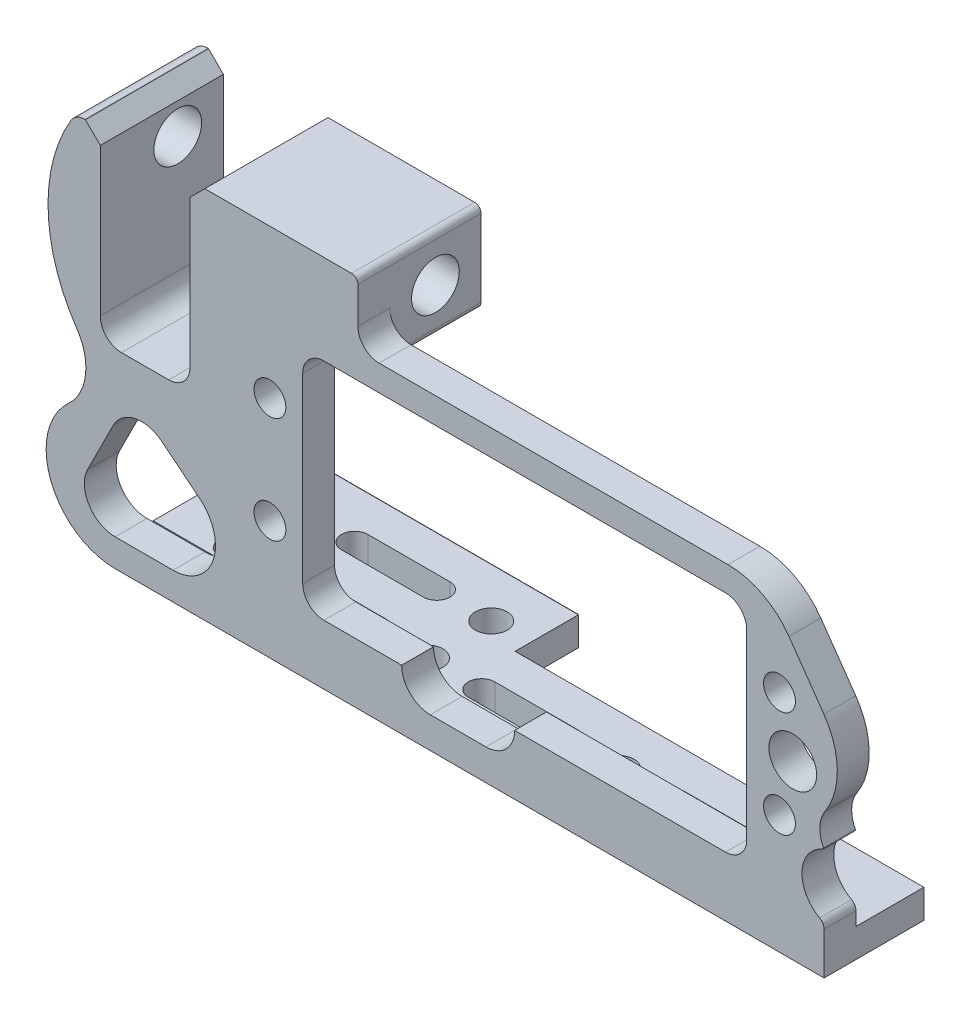
SolidWorks part; units mm, degrees
ref_plane "前视基准面" through (0, 0, 0) normal (0, 0, 1) x (1, 0, 0)
ref_plane "上视基准面" through (0, 0, 0) normal (0, 1, 0) x (1, 0, 0)
ref_plane "右视基准面" through (0, 0, 0) normal (1, 0, 0) x (0, 0, -1)
other "Configuration Table"
ref_plane "基准面1" through (0, 0, -7.725) normal (0, 0, -1) x (-1, 0, 0)
sketch "草图1" plane through (0, 0, -7.725) normal (0, 0, -1) x (-1, 0, 0)
  line L0 (33.1, 4.5) -> (24.8243, 4.5)
  line L1 (25.7249, 9.7195) -> (29.3009, 12.5896)
  line L2 (33.859, 11.5975) -> (36.2697, 6.8026)
  line L3 (33.6787, 2.6) -> (33.1, 2.6)
  line L4 (33.1, 2.6) -> (33.1, 4.5)
  line L5 (-33.1, 4.5) -> (-33.1, 0)
  line L6 (-33.1, 0) -> (33.6787, 0)
  line L7 (37.38, 35.225) -> (10.81, 35.225)
  line L8 (10.81, 35.225) -> (10.81, 29.2)
  line L9 (10.81, 29.2) -> (-27.6994, 29.2)
  line L10 (-27.6994, 29.2) -> (-33.0805, 21.515)
  arc A0 (24.8243, 4.5) -> (25.7249, 9.7195) centre (28.2287, 6.6) cw
  arc A1 (29.3009, 12.5896) -> (33.859, 11.5975) centre (31.1787, 10.25) cw
  arc A2 (36.2697, 6.8026) -> (33.6787, 2.6) centre (33.6787, 5.5) cw
  arc A3 (-33.1, 10.5) -> (-33.1, 4.5) centre (-34.2136, 7.5) cw
  arc A4 (33.6787, 0) -> (38.0616, 11.3) centre (33.6787, 6.5) ccw
  arc A5 (38.0616, 11.3) -> (37.2993, 17.8052) centre (41.433, 14.9924) cw
  arc A6 (37.2993, 17.8052) -> (37.38, 35.225) centre (24.4109, 26.575) ccw
  arc A7 (-33.0805, 21.515) -> (-33.1926, 13.65) centre (-27.3464, 17.5) ccw
  arc A8 (-33.1926, 13.65) -> (-33.1, 10.5) centre (-35.6981, 12) cw
extrude "凸台-拉伸1" add sketch "草图1" against normal blind 15.45
sketch "草图2" plane through (0, 0, 7.725) normal (0, 0, 1) x (1, 0, 0)
  line L0 (-33.1, 2.7) -> (-33.1, 2.6)
  line L1 (-33.1, 2.6) -> (-28.2287, 2.6)
  line L2 (-24.8243, 4.5) -> (-33.1, 4.5)
  line L3 (-33.1, 4.5) -> (-33.1, 2.7)
  arc A0 (-28.2287, 2.6) -> (-24.8243, 4.5) centre (-28.2287, 6.6) ccw
extrude "切除-拉伸1" cut sketch "草图2" against normal blind 3
sketch "草图3" plane through (0, 0, -7.725) normal (0, 0, -1) x (-1, 0, 0)
  line L0 (37.38, 35.225) -> (10.81, 35.225)
  line L1 (10.81, 35.225) -> (10.81, 29.2)
  line L2 (10.81, 29.2) -> (-27.6994, 29.2)
  line L3 (-27.6994, 29.2) -> (-33.0805, 21.515)
  line L4 (-33.1, 4.5) -> (24.8243, 4.5)
  line L5 (25.7249, 9.7195) -> (29.3009, 12.5896)
  line L6 (33.859, 11.5975) -> (36.2697, 6.8026)
  line L7 (33.6787, 2.6) -> (33.1, 2.6)
  line L8 (33.1, 2.6) -> (33.1, 0)
  line L9 (33.1, 0) -> (33.6787, 0)
  arc A0 (33.6787, 0) -> (38.0616, 11.3) centre (33.6787, 6.5) ccw
  arc A1 (38.0616, 11.3) -> (37.2993, 17.8052) centre (41.433, 14.9924) cw
  arc A2 (37.2993, 17.8052) -> (37.38, 35.225) centre (24.4109, 26.575) ccw
  arc A3 (-33.0805, 21.515) -> (-33.1926, 13.65) centre (-27.3464, 17.5) ccw
  arc A4 (-33.1926, 13.65) -> (-33.1, 10.5) centre (-35.6981, 12) cw
  arc A5 (-33.1, 10.5) -> (-33.1, 4.5) centre (-34.2136, 7.5) cw
  arc A6 (24.8243, 4.5) -> (25.7249, 9.7195) centre (28.2287, 6.6) cw
  arc A7 (29.3009, 12.5896) -> (33.859, 11.5975) centre (31.1787, 10.25) cw
  arc A8 (36.2697, 6.8026) -> (33.6787, 2.6) centre (33.6787, 5.5) cw
extrude "切除-拉伸2" cut sketch "草图3" against normal blind 3.85
ref_plane "基准面2" through (0, 5.625, 0) normal (0, -1, 0) x (1, 0, 0)
sketch "草图4" plane through (0, 5.625, 0) normal (0, -1, 0) x (1, 0, 0)
  line L0 (-16.01, -3.875) -> (25.81, -3.875)
  line L1 (25.81, -3.875) -> (25.81, 7.725)
  line L2 (25.81, 7.725) -> (-16.01, 7.725)
  line L3 (-16.01, 7.725) -> (-16.01, -3.875)
extrude "切除-拉伸3" cut sketch "草图4" against normal blind 21.15
sketch "草图5" plane through (0, 0, -3.875) normal (0, 0, -1) x (-1, 0, 0)
  line L0 (-33.1, 4.5) -> (24.8243, 4.5)
  line L1 (25.7249, 9.7195) -> (29.3009, 12.5896)
  line L2 (33.859, 11.5975) -> (36.2697, 6.8026)
  line L3 (33.6787, 2.6) -> (33.1, 2.6)
  line L4 (33.1, 2.6) -> (33.1, 0)
  line L5 (33.1, 0) -> (33.6787, 0)
  line L6 (36.4923, 14.225) -> (31.8022, 14.225)
  line L7 (25.2221, 26.775) -> (16.01, 26.775)
  line L8 (16.01, 26.775) -> (16.01, 5.625)
  line L9 (16.01, 5.625) -> (-25.81, 5.625)
  line L10 (-25.81, 5.625) -> (-25.81, 26.775)
  line L11 (-25.81, 26.775) -> (10.81, 26.775)
  line L12 (10.81, 26.775) -> (10.81, 29.2)
  line L13 (10.81, 29.2) -> (-27.6994, 29.2)
  line L14 (-27.6994, 29.2) -> (-33.0805, 21.515)
  arc A0 (24.8243, 4.5) -> (25.7249, 9.7195) centre (28.2287, 6.6) cw
  arc A1 (29.3009, 12.5896) -> (33.859, 11.5975) centre (31.1787, 10.25) cw
  arc A2 (36.2697, 6.8026) -> (33.6787, 2.6) centre (33.6787, 5.5) cw
  arc A3 (33.6787, 0) -> (38.0616, 11.3) centre (33.6787, 6.5) ccw
  arc A4 (38.0616, 11.3) -> (36.4923, 14.225) centre (41.433, 14.9924) cw
  arc A5 (31.8022, 14.225) -> (25.2221, 26.775) centre (31.8022, 22.225) cw
  arc A6 (-33.0805, 21.515) -> (-33.1926, 13.65) centre (-27.3464, 17.5) ccw
  arc A7 (-33.1926, 13.65) -> (-33.1, 10.5) centre (-35.6981, 12) cw
  arc A8 (-33.1, 10.5) -> (-33.1, 4.5) centre (-34.2136, 7.5) cw
extrude "切除-拉伸4" cut sketch "草图5" against normal blind 8.6
sketch "草图6" plane through (0, 4.5, 0) normal (0, 1, 0) x (-1, 0, 0)
  line L0 (-33.1, 4.725) -> (-33.1, -7.725)
  line L1 (-33.1, -7.725) -> (33.1, -7.725)
  line L2 (33.1, -7.725) -> (33.1, 4.725)
  line L3 (33.1, 4.725) -> (27.3399, 4.725)
  line L4 (27.3399, 4.725) -> (-33.1, 4.725)
extrude "切除-拉伸5" cut sketch "草图6" against normal blind 1.8
sketch "草图7" plane through (0, 0, 4.725) normal (0, 0, -1) x (-1, 0, 0)
  line L0 (6.69, 5.625) -> (-3.95, 5.625)
  line L1 (-1.25, 2.925) -> (3.99, 2.925)
  arc A0 (-3.95, 5.625) -> (-1.25, 2.925) centre (-1.25, 5.625) ccw
  arc A1 (3.99, 2.925) -> (6.69, 5.625) centre (3.99, 5.625) ccw
extrude "切除-拉伸6" cut sketch "草图7" against normal through all
sketch "草图8" plane through (0, 0, 0) normal (0, -1, 0) x (1, 0, 0)
  line L0 (33.1, -1.675) -> (-5.4, -1.675)
  line L1 (-5.4, -1.675) -> (-5.4, -7.725)
  line L2 (-5.4, -7.725) -> (33.1, -7.725)
  line L3 (33.1, -7.725) -> (33.1, -1.675)
extrude "切除-拉伸7" cut sketch "草图8" against normal through all
sketch "草图9" plane through (0, 0, 7.725) normal (0, 0, 1) x (1, 0, 0)
  line L0 (-26.63, 35.225) -> (-36.48, 35.225)
  line L1 (-36.48, 35.225) -> (-35.08, 33.825)
  line L2 (-35.08, 33.825) -> (-35.08, 17.925)
  line L3 (-35.08, 17.925) -> (-26.63, 17.925)
  line L4 (-26.63, 17.925) -> (-26.63, 35.225)
extrude "切除-拉伸8" cut sketch "草图9" against normal through all
sketch "草图10" plane through (0, 2.7, 0) normal (0, 1, 0) x (-1, 0, 0)
  line L0 (3.865, 4.275) -> (-3.865, 4.275)
  line L1 (-3.865, 1.775) -> (3.865, 1.775)
  arc A0 (-3.865, 4.275) -> (-3.865, 1.775) centre (-3.865, 3.025) ccw
  arc A1 (3.865, 1.775) -> (3.865, 4.275) centre (3.865, 3.025) ccw
extrude "切除-拉伸9" cut sketch "草图10" against normal through all
sketch "草图11" plane through (0, 2.7, 0) normal (0, 1, 0) x (-1, 0, 0)
  line L0 (-14.135, 4.275) -> (-21.865, 4.275)
  line L1 (-21.865, 1.775) -> (-14.135, 1.775)
  arc A0 (-21.865, 4.275) -> (-21.865, 1.775) centre (-21.865, 3.025) ccw
  arc A1 (-14.135, 1.775) -> (-14.135, 4.275) centre (-14.135, 3.025) ccw
extrude "切除-拉伸10" cut sketch "草图11" against normal through all
sketch "草图12" plane through (0, 2.7, 0) normal (0, 1, 0) x (-1, 0, 0)
  line L0 (14.135, -4.275) -> (21.865, -4.275)
  line L1 (21.865, -1.775) -> (14.135, -1.775)
  arc A0 (14.135, -1.775) -> (14.135, -4.275) centre (14.135, -3.025) ccw
  arc A1 (21.865, -4.275) -> (21.865, -1.775) centre (21.865, -3.025) ccw
extrude "切除-拉伸11" cut sketch "草图12" against normal through all
sketch "草图13" plane through (0, 0, 0) normal (0, -1, 0) x (1, 0, 0)
  line L0 (-14.135, 4.275) -> (-21.865, 4.275)
  line L1 (-21.865, 1.775) -> (-14.135, 1.775)
  arc A0 (-21.865, 4.275) -> (-21.865, 1.775) centre (-21.865, 3.025) ccw
  arc A1 (-14.135, 1.775) -> (-14.135, 4.275) centre (-14.135, 3.025) ccw
extrude "切除-拉伸12" cut sketch "草图13" against normal up to next
hole_wizard "Ø4.5 (4.5) 直径孔1" positions "草图15" profile "草图14" hole size "Ø4.5" standard "ANSI Metric"
sketch "草图15" plane through (0, 0, 7.725) normal (0, 0, 1) x (1, 0, 0)
  point P0 (30.15, 16.2)
sketch "草图14" plane through (30.15, 16.2, 7.725) normal (1, 0, 0) x (0, -1, 0)
  line L0 (0, 0) -> (0, 15.45)
  line L1 (0, 15.45) -> (2.25, 15.45)
  line L2 (2.25, 15.45) -> (2.25, 0)
  line L5 (2.25, 0) -> (0, 0)
  line L11 (0, -6.35) -> (0, 107.95) construction
  dimension "通孔孔直径" = 4.5
  dimension "通孔孔深度" = 15.45
hole_wizard "Ø3.0 (3) 直径孔1" positions "草图17" profile "草图16" hole size "Ø3.0" standard "ANSI Metric"
sketch "草图17" plane through (0, 0, 7.725) normal (0, 0, 1) x (1, 0, 0)
  point P0 (-19.1, 11.2)
  point P1 (28.9, 11.2)
  point P2 (-19.1, 21.2)
  point P3 (28.9, 21.2)
sketch "草图16" plane through (-19.1, 11.2, 7.725) normal (1, 0, 0) x (0, -1, 0)
  line L0 (0, 0) -> (0, 15.45)
  line L1 (0, 15.45) -> (1.5, 15.45)
  line L2 (1.5, 15.45) -> (1.5, 0)
  line L5 (1.5, 0) -> (0, 0)
  line L11 (0, -6.35) -> (0, 107.95) construction
  dimension "通孔孔直径" = 3
  dimension "通孔孔深度" = 15.45
hole_wizard "Ø4.5 (4.5) 直径孔2" positions "草图19" profile "草图18" hole size "Ø4.5" standard "ANSI Metric"
sketch "草图19" plane through (-10.81, 0, 0) normal (1, 0, 0) x (0, 0, -1)
  point P0 (-0.425, 30.925)
sketch "草图18" plane through (-10.81, 30.925, 0.425) normal (0, 1, 0) x (0, 0, -1)
  line L0 (0, 0) -> (0, 15.82)
  line L1 (0, 15.82) -> (2.25, 15.82)
  line L2 (2.25, 15.82) -> (2.25, 0)
  line L5 (2.25, 0) -> (0, 0)
  line L11 (0, -6.35) -> (0, 107.95) construction
  dimension "通孔孔直径" = 4.5
  dimension "通孔孔深度" = 15.82
hole_wizard "Ø3.0 (3) 直径孔2" positions "草图21" profile "草图20" hole size "Ø3.0" standard "ANSI Metric"
sketch "草图21" plane through (0, 0, 0) normal (0, -1, 0) x (-1, 0, 0)
  point P0 (-9, -3.025)
  point P1 (9, -3.025)
  point P2 (9, 3.025)
  point P3 (-27, -3.025)
sketch "草图20" plane through (9, 0, 3.025) normal (1, 0, 0) x (0, 0, -1)
  line L0 (0, 0) -> (0, 35.225)
  line L1 (0, 35.225) -> (1.5, 35.225)
  line L2 (1.5, 35.225) -> (1.5, 0)
  line L5 (1.5, 0) -> (0, 0)
  line L11 (0, -6.35) -> (0, 107.95) construction
  dimension "通孔孔直径" = 3
  dimension "通孔孔深度" = 35.225
hole_wizard "Ø3.0 (3) 直径孔3" positions "草图23" profile "草图22" hole size "Ø3.0" standard "ANSI Metric"
sketch "草图23" plane through (0, 0, 0) normal (0, -1, 0) x (-1, 0, 0)
  point P0 (27, -3.025)
  point P1 (27, 3.025)
sketch "草图22" plane through (-27, 0, 3.025) normal (1, 0, 0) x (0, 0, -1)
  line L0 (0, 0) -> (0, 2.7)
  line L1 (0, 2.7) -> (1.5, 2.7)
  line L2 (1.5, 2.7) -> (1.5, 0)
  line L5 (1.5, 0) -> (0, 0)
  line L11 (0, -6.35) -> (0, 107.95) construction
  dimension "通孔孔直径" = 3
  dimension "通孔孔深度" = 2.7
hole_wizard "Ø4.5 (4.5) 直径孔3" positions "草图25" profile "草图24" hole size "Ø4.5" standard "ANSI Metric"
sketch "草图25" plane through (-35.08, 0, 0) normal (1, 0, 0) x (0, 0, -1)
  point P0 (-0.425, 30.925)
sketch "草图24" plane through (-35.08, 30.925, 0.425) normal (0, 1, 0) x (0, 0, -1)
  line L0 (0, 0) -> (0, 5.0987)
  line L1 (0, 5.0987) -> (2.25, 5.0987)
  line L2 (2.25, 5.0987) -> (2.25, 0)
  line L5 (2.25, 0) -> (0, 0)
  line L11 (0, -6.35) -> (0, 107.95) construction
  dimension "通孔孔直径" = 4.5
  dimension "通孔孔深度" = 5.0987
chamfer "倒角1" distance 1.4 angle 45 1 edges at (-26.63, 35.225, 1.925)
fillet "圆角1" radius 0.1 5 edges at (-5.4, 1.35, -7.725) (-19.25, 0, -7.725) (-19.25, 2.7, -7.725) (-33.1, 1.35, -7.725) (33.1, 10.5, 6.225)
fillet "圆角2" radius 0.6 3 edges at (-10.81, 35.225, 1.925) (-36.4923, 14.225, 0.425) (-10.81, 26.775, 0.425)
fillet "圆角3" radius 0.8 1 edges at (33.1, 4.5, 6.225)
fillet "圆角4" radius 1.5 1 edges at (-37.38, 35.225, 1.925)
fillet "圆角5" radius 2 7 edges at (-10.81, 29.2, 6.225) (25.81, 5.625, 6.225) (-26.63, 17.925, 1.925) (-16.01, 5.625, 6.225) (-16.01, 26.775, 6.225) (25.81, 26.775, 6.225) (-35.08, 17.925, 1.925)
fillet "圆角6" radius 5 1 edges at (-25.2221, 26.775, 0.425)
fillet "圆角7" radius 7 1 edges at (27.6994, 29.2, 6.225)
sketch "草图26" plane through (0, 17.925, 0) normal (0, 1, 0) x (1, 0, 0)
  line L1 (-33.08, -1.925) -> (-28.63, -1.925)
  line L3 (-30.855, 3.875) -> (-30.855, -7.725)
  line L4 (-33.08, -7.725) -> (-28.63, -7.725)
  line L5 (-28.63, -7.725) -> (-28.63, 3.875)
  line L6 (-28.63, 3.875) -> (-33.08, 3.875)
  line L7 (-33.08, 3.875) -> (-33.08, -7.725)
  line L8 (-33.08, -7.725) -> (-28.63, -7.725)
  line L9 (-28.63, -7.725) -> (-28.63, 3.875)
  line L10 (-28.63, 3.875) -> (-33.08, 3.875)
  line L11 (-33.08, 3.875) -> (-33.08, -7.725)
  point P8 (-30.855, -1.925)
  dimension "D1" = 0
sketch "草图27" plane through (0, 0, 0) normal (0, -1, 0) x (1, 0, 0)
  line L0 (-30.855, -3.875) -> (-30.855, 7.725) construction
  line L1 (-33.08, 1.925) -> (-28.63, 1.925) construction
  line L2 (-30.855, -3.875) -> (-30.855, 7.725)
  line L3 (-33.08, 1.925) -> (-28.63, 1.925)
  circle A0 centre (27, 3.025) radius 1.5 construction
  circle A1 centre (9, 3.025) radius 1.5 construction
  circle A2 centre (-9, -3.025) radius 1.5 construction
  circle A3 centre (-9, 3.025) radius 1.5 construction
  circle A4 centre (-27, -3.025) radius 1.5 construction
  circle A5 centre (-27, 3.025) radius 1.5 construction
  circle A6 centre (27, 3.025) radius 1.5
  circle A7 centre (9, 3.025) radius 1.5
  circle A8 centre (-9, -3.025) radius 1.5
  circle A9 centre (-9, 3.025) radius 1.5
  circle A10 centre (-27, -3.025) radius 1.5
  circle A11 centre (-27, 3.025) radius 1.5
  point P4 (-30.855, 1.925)
